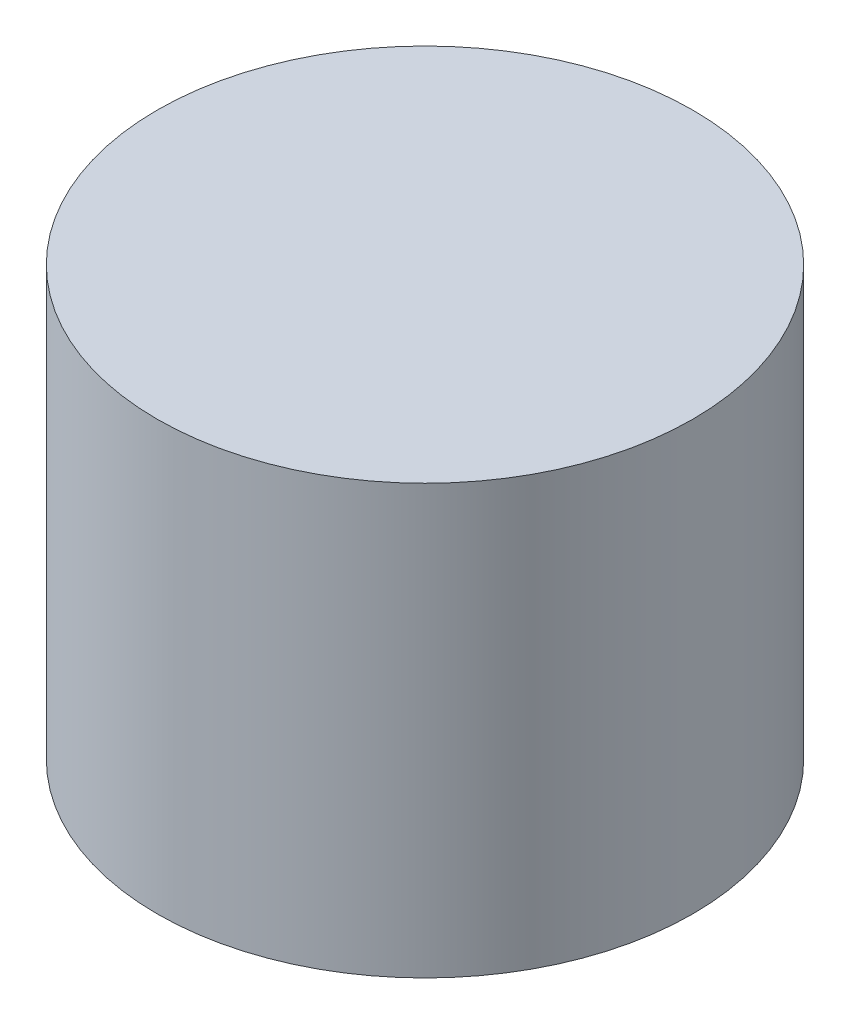
SolidWorks part; units mm, degrees
ref_plane "Plan de face" through (0, 0, 0) normal (0, 0, 1) x (1, 0, 0)
ref_plane "Plan de dessus" through (0, 0, 0) normal (0, 1, 0) x (1, 0, 0)
ref_plane "Plan de droite" through (0, 0, 0) normal (1, 0, 0) x (0, 0, -1)
sketch "Esquisse1" plane through (0, 0, 0) normal (0, 1, 0) x (1, 0, 0)
  circle A0 centre (0, 0) radius 2.5
extrude "Boss.-Extru.1" add sketch "Esquisse1" along normal blind 4
